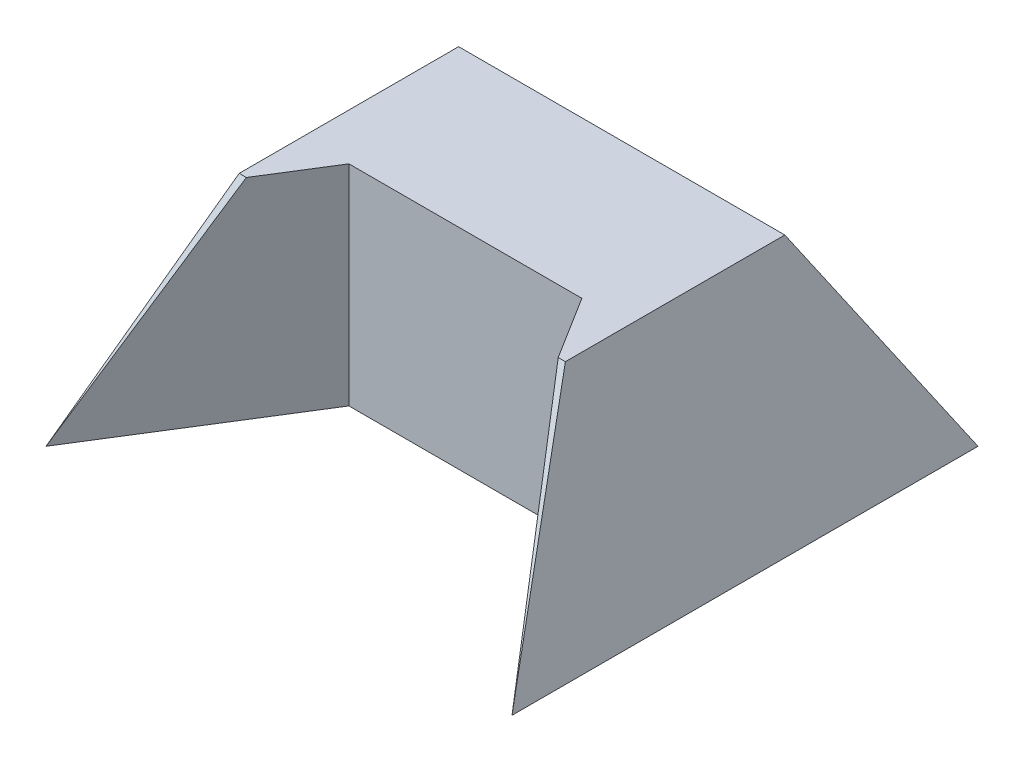
SolidWorks part; units mm, degrees
ref_plane "Ebene vorne" through (0, 0, 0) normal (0, 0, 1) x (1, 0, 0)
ref_plane "Ebene oben" through (0, 0, 0) normal (0, 1, 0) x (1, 0, 0)
ref_plane "Ebene rechts" through (0, 0, 0) normal (1, 0, 0) x (0, 0, -1)
sketch "Skizze1" plane through (0, 0, 0) normal (0, 0, 1) x (1, 0, 0)
  line L0 (0, 0) -> (100, 0)
  line L1 (100, 0) -> (85, 45)
  line L2 (85, 45) -> (15, 45)
  line L3 (15, 45) -> (0, 0)
  dimension "D1" = 100
  dimension "D2" = 15
  dimension "D3" = 15
  dimension "D4" = 45
extrude "Grundkörper" add sketch "Skizze1" against normal blind 100
sketch "Skizze2" plane through (0, 0, 0) normal (1, 0, 0) x (0, 0, -1)
  line L0 (100, 0) -> (73.5442, 45)
  line L1 (100, 45) -> (0, 45) construction
  line L2 (73.5442, 45) -> (100, 45)
  line L3 (100, 45) -> (100, 0)
extrude "Schraegen_vorne" cut sketch "Skizze2" along normal blind 100
ref_plane "Ebene1" through (0, 0, -50) normal (0, 0, 1) x (1, 0, 0)
mirror "Spiegel_Schraege_hinten" about plane through (0, 0, -50) normal (0, 0, 1) of "Schraegen_vorne"
sketch "Skizze4" plane through (0, 0, 0) normal (0, -1, 0) x (1, 0, 0)
  line L0 (100, 0) -> (75, -40)
  line L1 (75, -40) -> (25, -40)
  line L2 (25, -40) -> (0, 0)
  line L3 (0, 0) -> (100, 0)
  dimension "D1" = 50
  dimension "D2" = 25
  dimension "D3" = 40
extrude "Schnitt-Linear austragen4" cut sketch "Skizze4" against normal blind 45
sketch "Skizze6" plane through (0, 0, -40) normal (0, 0, 1) x (1, 0, 0)
  circle A0 centre (50, 20) radius 15
